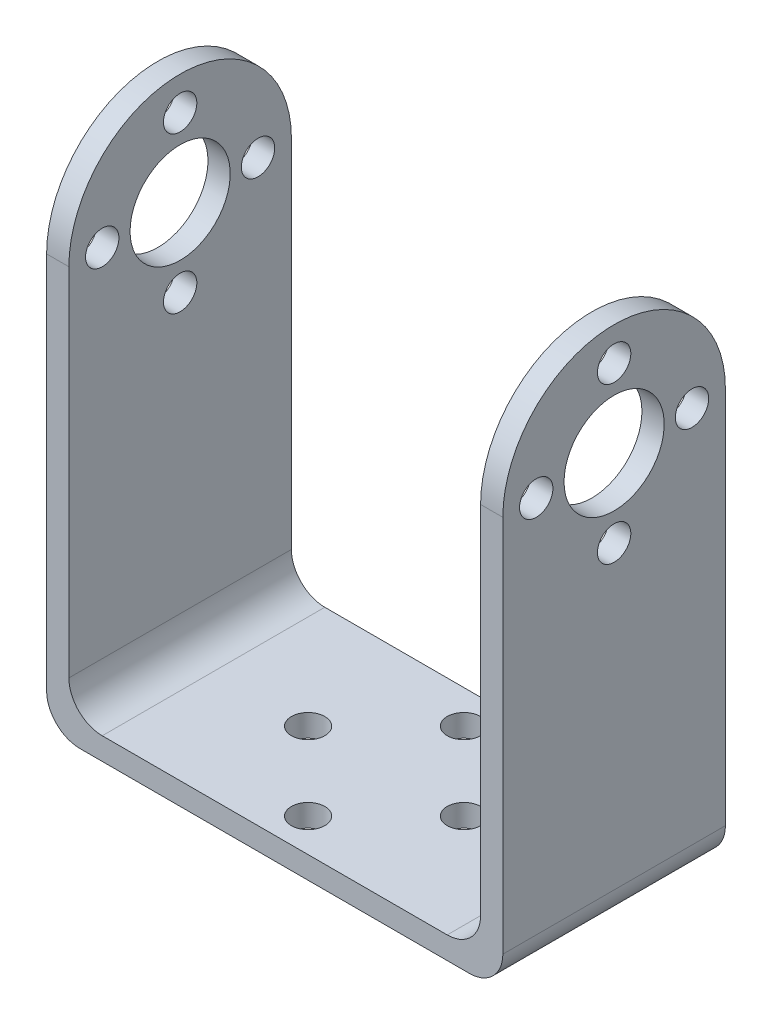
SolidWorks part; units mm, degrees
ref_plane "前视基准面" through (0, 0, 0) normal (0, 0, 1) x (1, 0, 0)
ref_plane "上视基准面" through (0, 0, 0) normal (0, 1, 0) x (1, 0, 0)
ref_plane "右视基准面" through (0, 0, 0) normal (1, 0, 0) x (0, 0, -1)
sketch "草图1" plane through (0, 0, 0) normal (0, 1, 0) x (1, 0, 0)
  line L1 (-20.5, 10) -> (-12.5, 10)
  line L2 (-20.5, 10) -> (-20.5, -10)
  line L3 (-20.5, -10) -> (-12.5, -10)
  line L4 (20.5, 10) -> (20.5, -10)
  line L5 (-20.5, 10) -> (20.5, -10) construction
  line L6 (-20.5, -10) -> (20.5, 10) construction
  line L13 (12.5, -10) -> (20.5, -10)
  line L15 (12.5, 10) -> (20.5, 10)
  line L16 (12.5, 10) -> (-12.5, 10)
  line L17 (-12.5, -10) -> (12.5, -10)
  point P0 (0, 0)
  point P6 (0, 0)
  dimension "D1" = 41
  dimension "D2" = 20
extrude "凸台-拉伸1" add sketch "草图1" along normal blind 2
sketch "草图2" plane through (0, 2, 0) normal (0, 1, 0) x (1, 0, 0)
  line L0 (-20.5, -10) -> (20.5, -10) construction
  line L1 (-20.5, 10) -> (-18.5, 10)
  line L2 (-20.5, 10) -> (-20.5, -10)
  line L3 (-20.5, -10) -> (-18.5, -10)
  line L4 (-18.5, 10) -> (-18.5, -10)
  line L5 (-20.5, -10) -> (20.5, -10) construction
  line L6 (20.5, 10) -> (18.5, 10)
  line L7 (20.5, 10) -> (20.5, -10)
  line L8 (20.5, -10) -> (18.5, -10)
  line L9 (18.5, 10) -> (18.5, -10)
  dimension "D1" = 2
  dimension "D2" = 2
extrude "凸台-拉伸2" add sketch "草图2" along normal blind 60
fillet "圆角1" radius 3 4 edges at (-20.5, 0, 0) (-18.5, 2, 0) (18.5, 2, 0) (20.5, 0, 0)
sketch "草图6" plane through (-20.5, 0, 0) normal (-1, 0, 0) x (0, 0, 1)
  line L0 (0, 47.2402) -> (0, -12.4121) construction
  line L1 (26.009, 2) -> (-24.6618, 2) construction
  line L2 (-10, 62) -> (-10, 3) construction
  line L3 (10, 62) -> (10, 3) construction
  line L4 (-10, 37) -> (-10, 62)
  line L5 (-10, 62) -> (10, 62)
  line L6 (10, 62) -> (10, 37)
  arc A0 (-10, 37) -> (10, 37) centre (0, 37) cw
  circle A1 centre (0, 37) radius 4.5
  circle A2 centre (0, 37) radius 7 construction
  circle A3 centre (0, 30) radius 1.5
  circle A10 centre (-7, 37) radius 1.5
  circle A11 centre (0, 44) radius 1.5
  circle A12 centre (7, 37) radius 1.5
  point P20 (0, 0)
  point P21 (0, 37)
  point P29 (0, 37)
  point P30 (0, 37)
  point P31 (0, 37)
  dimension "D2" = 9
  dimension "D4" = 14
  dimension "D5" = 3
  dimension "D1" = 2
  dimension "D3" = 35
  dimension "D6" = 4
extrude "切除-拉伸2" cut sketch "草图6" against normal through all
sketch "草图7" plane through (0, 0, 0) normal (0, -1, 0) x (1, 0, 0)
  line L0 (23.2283, 0) -> (-27.1494, 0) construction
  line L1 (0, -13.6173) -> (0, 13.1485) construction
  circle A0 centre (0, 0) radius 7 construction
  circle A1 centre (-7, 0) radius 1.5
  circle A2 centre (0, 7) radius 1.5
  circle A3 centre (7, 0) radius 1.5
  circle A4 centre (0, -7) radius 1.5
  point P18 (0, 0)
  dimension "D1" = 14
  dimension "D2" = 3
  dimension "D3" = 4
extrude "切除-拉伸3" cut sketch "草图7" against normal blind 10
